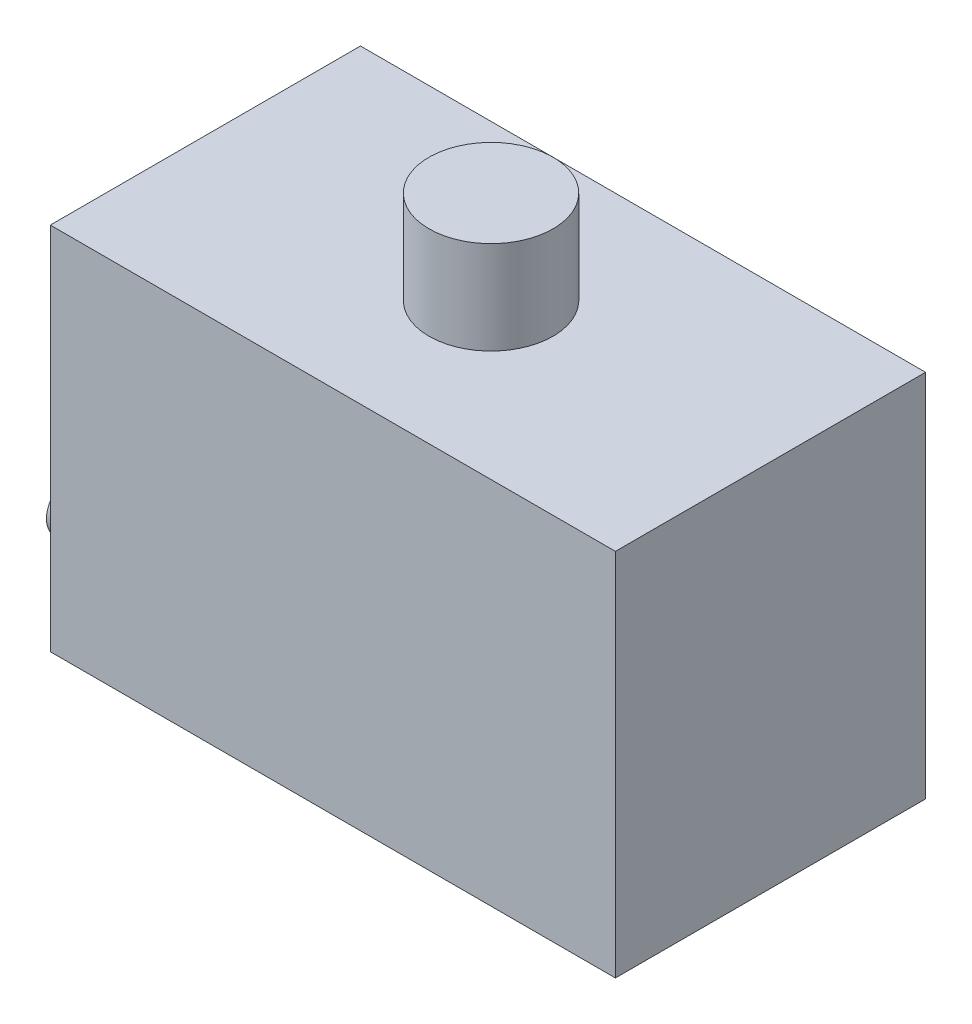
SolidWorks part; units mm, degrees
ref_plane "Front Plane" through (0, 0, 0) normal (0, 0, 1) x (1, 0, 0)
ref_plane "Top Plane" through (0, 0, 0) normal (0, 1, 0) x (1, 0, 0)
ref_plane "Right Plane" through (0, 0, 0) normal (1, 0, 0) x (0, 0, -1)
sketch "Sketch1" plane through (0, 0, 0) normal (0, 0, 1) x (1, 0, 0)
  line L1 (-46.0503, 29.282) -> (45.0492, 29.282)
  line L2 (-46.0503, 29.282) -> (-46.0503, -30.283)
  line L3 (-46.0503, -30.283) -> (45.0492, -30.283)
  line L4 (45.0492, 29.282) -> (45.0492, -30.283)
extrude "Boss-Extrude1" add sketch "Sketch1" along normal blind 50
sketch "Sketch2" plane through (-46.0503, 0, 0) normal (-1, 0, 0) x (0, 0, 1)
  circle A0 centre (41.5133, -16.4062) radius 4.1093
extrude "Boss-Extrude2" add sketch "Sketch2" along normal blind 5
sketch "Sketch4" plane through (0, 29.282, 0) normal (0, 1, 0) x (1, 0, 0)
  circle A0 centre (0, -25) radius 10
  dimension "D1" = 20
extrude "Boss-Extrude3" add sketch "Sketch4" along normal blind 15
